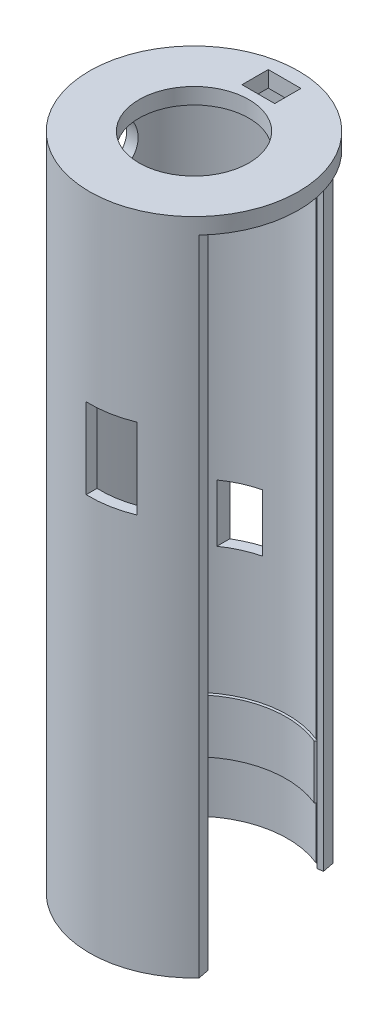
SolidWorks part; units mm, degrees
ref_plane "Front Plane" through (0, 0, 0) normal (0, 0, 1) x (1, 0, 0)
ref_plane "Top Plane" through (0, 0, 0) normal (0, 1, 0) x (1, 0, 0)
ref_plane "Right Plane" through (0, 0, 0) normal (1, 0, 0) x (0, 0, -1)
sketch "Sketch12" plane through (0, 0, 0) normal (0, 1, 0) x (1, 0, 0)
  line L0 (8.6347, 15.5184) -> (8.2084, 17.6882)
  line L1 (8.6347, 15.5184) -> (7.568, 15.3643)
  line L2 (7.568, 15.3643) -> (7.3752, 16.3458)
  line L3 (7.3752, 16.3458) -> (6.6214, 16.1774)
  line L4 (12.7902, -11.4418) -> (13.8366, -11.1839)
  line L5 (13.8366, -11.1839) -> (14.2509, -13.3102)
  line L6 (12.7902, -11.4418) -> (12.9718, -12.3819)
  line L7 (12.9718, -12.3819) -> (12.218, -12.5008)
  arc A0 (8.2084, 17.6882) -> (14.2509, -13.3102) centre (0, 0) ccw
  arc A2 (6.6214, 16.1774) -> (12.218, -12.5008) centre (0, 0) ccw
  dimension "D1" = 17.48
  dimension "D2" = 19.5
  dimension "D3" = 2.1663
  dimension "D4" = 0.7538
  dimension "D5" = 0.7538
  dimension "D6" = 2.1698
extrude "Boss-Extrude1" add sketch "Sketch12" along normal blind 120
sketch "Sketch13" plane through (0, 120, 0) normal (0, 1, 0) x (1, 0, 0)
  circle A0 centre (0, 0) radius 19.5
  circle A1 centre (0, 0) radius 10.25
  dimension "D1" = 20.5
  dimension "D2" = 39
extrude "Boss-Extrude3" add sketch "Sketch13" along normal blind 3
sketch "Sketch16" plane through (0, 123, 0) normal (0, 1, 0) x (1, 0, 0)
  line L0 (0, 0) -> (0, 19.5) construction
  line L2 (3.05, 12) -> (-3.05, 12)
  line L3 (3.05, 12) -> (3.05, 16.9)
  line L4 (3.05, 16.9) -> (-3.05, 16.9)
  line L5 (-3.05, 12) -> (-3.05, 16.9)
  line L6 (3.05, 12) -> (-3.05, 16.9) construction
  line L7 (3.05, 16.9) -> (-3.05, 12) construction
  circle A0 centre (0, 0) radius 19.5 construction
  point P6 (0, 14.45)
  dimension "D1" = 4.9
  dimension "D2" = 6.1
  dimension "D3" = 12
extrude "Cut-Extrude1" cut sketch "Sketch16" against normal blind 5
sketch "Sketch17" plane through (0, 0, 0) normal (0, 0, 1) x (1, 0, 0)
  line L1 (-0.6234, 88.7322) -> (7.3766, 88.7322)
  line L2 (-0.6234, 88.7322) -> (-0.6234, 73.7322)
  line L3 (-0.6234, 73.7322) -> (7.3766, 73.7322)
  line L4 (7.3766, 88.7322) -> (7.3766, 73.7322)
  line L5 (-0.6234, 88.7322) -> (7.3766, 73.7322) construction
  line L6 (-0.6234, 73.7322) -> (7.3766, 88.7322) construction
  point P0 (3.3766, 81.2322)
  dimension "D1" = 8
  dimension "D2" = 15
extrude "Cut-Extrude2" cut sketch "Sketch17" along normal blind 150
sketch "Sketch18" plane through (0, 0, 0) normal (1, 0, 0) x (0, 0, -1)
  circle A0 centre (0, 110.7711) radius 6
  point P2 (0, 110.7711)
  point P3 (0, 0)
  point P4 (0, 110.7711)
  dimension "D1" = 12
extrude "Cut-Extrude5" cut sketch "Sketch18" against normal blind 20 contours A0
sketch "Sketch21" plane through (0, 0, 0) normal (0, 0, 1) x (1, 0, 0)
  line L1 (-10.0416, 54.5009) -> (-4.1972, 54.5009)
  line L2 (-10.0416, 54.5009) -> (-10.0416, 43.7862)
  line L3 (-10.0416, 43.7862) -> (-4.1972, 43.7862)
  line L4 (-4.1972, 54.5009) -> (-4.1972, 43.7862)
  point P4 (0, 0)
  point P5 (-8.8635, 43.264)
  point P6 (0, 0)
  point P7 (0, 0)
  dimension "D1" = 5.8444
  dimension "D2" = 10.7146
extrude "Cut-Extrude6" cut sketch "Sketch21" against normal blind 120
ref_plane "Plane1" through (0, 10, 0) normal (0, -1, 0) x (-1, 0, 0)
sketch "Sketch24" plane through (0, 10, 0) normal (0, -1, 0) x (-1, 0, 0)
  line L16 (-8.6347, 15.5184) -> (-7.568, 15.3643)
  line L17 (-7.568, 15.3643) -> (-7.3752, 16.3458)
  line L18 (-7.3752, 16.3458) -> (-6.711, 15.718)
  line L19 (-12.218, -12.5008) -> (-12.9718, -12.3819)
  line L20 (-12.9718, -12.3819) -> (-12.7902, -11.4418)
  line L21 (-12.7902, -11.4418) -> (-13.8366, -11.1839)
  line L22 (-13.8366, -11.1839) -> (-14.2509, -13.3102)
  line L23 (-8.2084, 17.6882) -> (-8.6347, 15.5184)
  arc A6 (-12.218, -12.5008) -> (-6.711, 15.718) centre (-0.1957, -0.2002) ccw
  arc A7 (-14.2509, -13.3102) -> (-8.2084, 17.6882) centre (0, 0) ccw
  point P0 (0, 0)
  dimension "D2" = 17.2
  dimension "D1" = 19.5
extrude "Boss-Extrude4" add sketch "Sketch24" against normal blind 10
